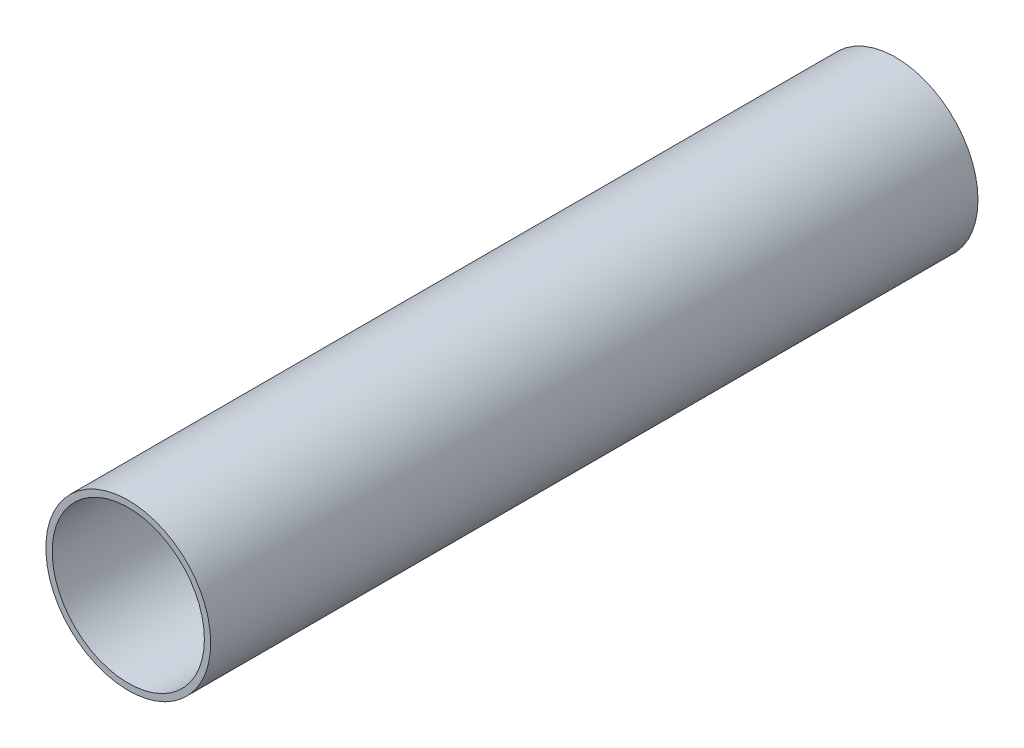
SolidWorks part; units mm, degrees
ref_plane "Front Plane" through (0, 0, 0) normal (0, 0, 1) x (1, 0, 0)
ref_plane "Top Plane" through (0, 0, 0) normal (0, 1, 0) x (1, 0, 0)
ref_plane "Right Plane" through (0, 0, 0) normal (1, 0, 0) x (0, 0, -1)
sketch "Sketch1" plane through (0, 0, 0) normal (0, 0, 1) x (1, 0, 0)
  circle A0 centre (0, 0) radius 26
  circle A1 centre (0, 0) radius 24
  dimension "D1" = 52
  dimension "D2" = 2
extrude "Boss-Extrude1" add sketch "Sketch1" along normal blind 242
